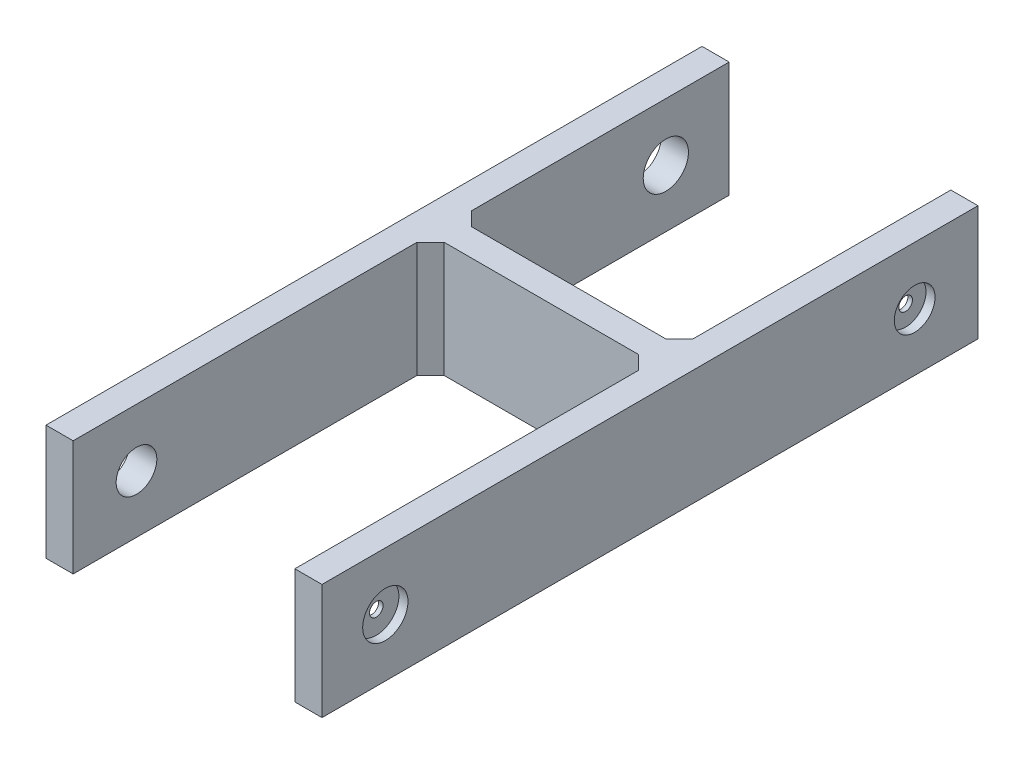
SolidWorks part; units mm, degrees
material "ABS"
ref_plane "Front Plane" through (0, 0, 0) normal (0, 0, 1) x (1, 0, 0)
ref_plane "Top Plane" through (0, 0, 0) normal (0, 1, 0) x (1, 0, 0)
ref_plane "Right Plane" through (0, 0, 0) normal (1, 0, 0) x (0, 0, -1)
other "Center of Mass"
sketch "Sketch1" plane through (0, 0, 0) normal (0, 1, 0) x (1, 0, 0)
  line L12 (6, -6) -> (55, -6)
  line L13 (55, -6) -> (55, -85)
  line L14 (55, -85) -> (61, -85)
  line L15 (61, -85) -> (61, 60)
  line L17 (0, 60) -> (0, -85)
  line L18 (0, -85) -> (6, -85)
  line L19 (6, -85) -> (6, -6)
  line L20 (6, 0) -> (55, 0)
  line L21 (0, 60) -> (6, 60)
  line L22 (6, 60) -> (6, 0)
  line L23 (55, 0) -> (55, 60)
  line L24 (55, 60) -> (61, 60)
  dimension "D1" = 6
  dimension "D2" = 6
  dimension "D3" = 79
  dimension "D4" = 60
  dimension "D5" = 49
extrude "Boss-Extrude1" add sketch "Sketch1" along normal blind 25.5
sketch "Sketch2" plane through (6, 0, 0) normal (1, 0, 0) x (0, 0, -1)
  line L0 (-85, 25.5) -> (-85, 0) construction
  line L2 (-85, 25.5) -> (60, 25.5) construction
  circle A0 centre (-71, 12.75) radius 4.5
  dimension "D2" = 9
  dimension "D3" = 12.75
  dimension "D1" = 14
extrude "Cut-Extrude1" cut sketch "Sketch2" against normal blind 25
sketch "Sketch3" plane through (55, 0, 0) normal (-1, 0, 0) x (0, 0, 1)
  circle A0 centre (71, 12.75) radius 1.5
  dimension "D1" = 3
extrude "Cut-Extrude2" cut sketch "Sketch3" against normal blind 10
sketch "Sketch4" plane through (61, 0, 0) normal (1, 0, 0) x (0, 0, -1)
  circle A0 centre (-71, 12.75) radius 5
  dimension "D1" = 10
extrude "Cut-Extrude3" cut sketch "Sketch4" against normal blind 2
sketch "Sketch5" plane through (55, 0, 0) normal (-1, 0, 0) x (0, 0, 1)
  line L1 (71, 19.25) -> (54, 15.75)
  line L2 (54, 9.75) -> (71, 6.25)
  arc A0 (71, 19.25) -> (71, 6.25) centre (71, 12.75) cw
  circle A1 centre (71, 12.75) radius 5 construction
  arc A2 (54, 15.75) -> (54, 9.75) centre (54, 12.75) ccw
  dimension "D2" = 1.5
  dimension "D1" = 13
  dimension "D3" = 17
  dimension "D4" = 6
extrude "Cut-Extrude4" cut sketch "Sketch5" against normal blind 3
sketch "Sketch6" plane through (55, 0, 0) normal (-1, 0, 0) x (0, 0, 1)
  line L3 (-29, 9.75) -> (-46, 6.25)
  line L4 (-46, 19.25) -> (-29, 15.75)
  line L5 (-60, 25.5) -> (-60, 0) construction
  line L6 (-60, 0) -> (0, 0) construction
  arc A2 (-29, 15.75) -> (-29, 9.75) centre (-29, 12.75) cw
  arc A3 (-46, 19.25) -> (-46, 6.25) centre (-46, 12.75) ccw
  point P4 (0, 0)
  point P5 (0, 0)
  point P6 (0, 0)
  point P7 (0, 0)
  point P14 (0, 0)
  point P15 (0, 0)
  point P16 (-33, 15.75)
  point P17 (-33, 9.75)
  point P18 (0, 0)
  dimension "D1" = 6.5
  dimension "D2" = 3
  dimension "D3" = 14
  dimension "D4" = 17
  dimension "D5" = 12.75
extrude "Cut-Extrude5" cut sketch "Sketch6" against normal blind 3
sketch "Sketch7" plane through (61, 0, 0) normal (1, 0, 0) x (0, 0, -1)
  circle A0 centre (46, 12.75) radius 4.5
  dimension "D1" = 9
extrude "Cut-Extrude6" cut sketch "Sketch7" against normal blind 2
sketch "Sketch8" plane through (61, 0, 0) normal (1, 0, 0) x (0, 0, -1)
  circle A0 centre (46, 12.75) radius 1.5
  dimension "D1" = 3
extrude "Cut-Extrude7" cut sketch "Sketch8" against normal through all both and the other way through all
sketch "Sketch9" plane through (0, 0, 0) normal (-1, 0, 0) x (0, 0, 1)
  circle A0 centre (-46, 12.75) radius 5
  dimension "D1" = 10
extrude "Cut-Extrude8" cut sketch "Sketch9" against normal blind 10
sketch "Sketch10" plane through (0, 25.5, 0) normal (0, 1, 0) x (1, 0, 0)
  line L3 (55, 0) -> (6, 0) construction
  line L9 (30.5, 0) -> (30.5, -6) construction
  line L10 (6, -6) -> (55, -6) construction
  line L11 (30.5, -3) -> (37.8663, -3) construction
  line L12 (9, -6) -> (6, -6)
  line L13 (6, -9) -> (9, -6)
  line L14 (6, -6) -> (6, -9)
  line L15 (6, 0) -> (6, 3)
  line L16 (6, 3) -> (9, 0)
  line L17 (9, 0) -> (6, 0)
  line L18 (52, 0) -> (55, 0)
  line L19 (55, 3) -> (52, 0)
  line L20 (55, 0) -> (55, 3)
  line L21 (55, -6) -> (55, -9)
  line L22 (55, -9) -> (52, -6)
  line L23 (52, -6) -> (55, -6)
  point P2 (0, 0)
  point P10 (0, 0)
  point P22 (0, 0)
  point P23 (0, 0)
  point P24 (9, -6)
  point P25 (9, -6)
  point P26 (6, -6)
  point P27 (0, 0)
  point P28 (0, 0)
extrude "Boss-Extrude2" add sketch "Sketch10" against normal up to surface (25.5 mm away) up to face at (30.5, 0, 9.3333)
